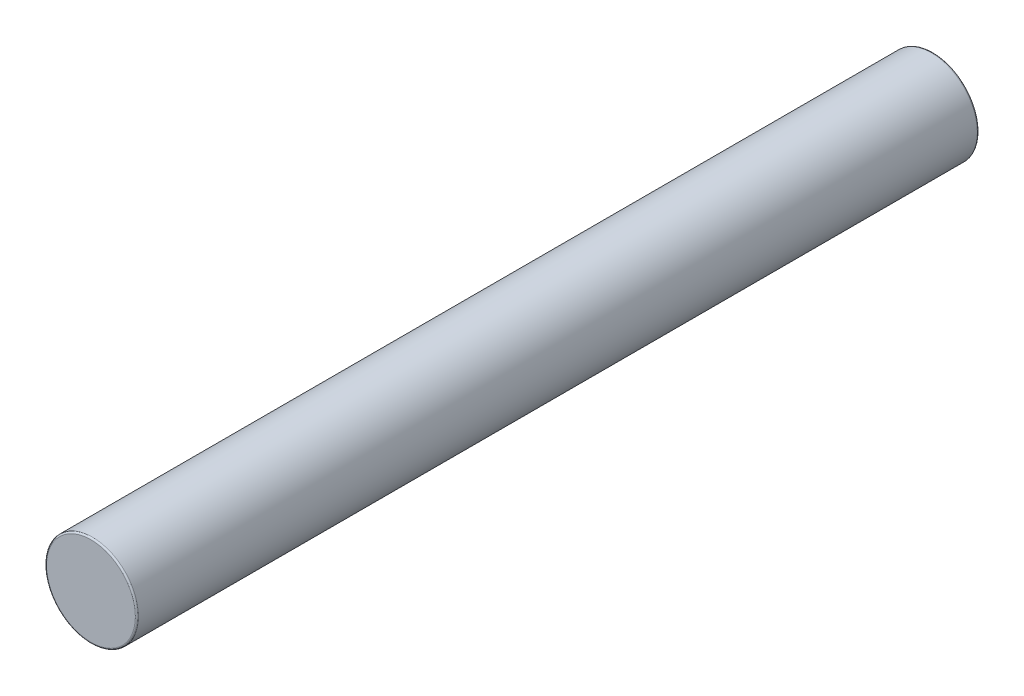
SolidWorks part; units mm, degrees
ref_plane "Спереди" through (0, 0, 0) normal (0, 0, 1) x (1, 0, 0)
ref_plane "Сверху" through (0, 0, 0) normal (0, 1, 0) x (1, 0, 0)
ref_plane "Справа" through (0, 0, 0) normal (1, 0, 0) x (0, 0, -1)
sketch "Эскиз1" plane through (0, 0, 0) normal (0, 0, 1) x (1, 0, 0)
  circle A0 centre (0, 0) radius 3
  dimension "D1" = 6
extrude "Бобышка-Вытянуть1" add sketch "Эскиз1" along normal blind 55
fillet "Скругление1" radius 0.1 2 edges at (3, 0, 0) (3, 0, 55)
